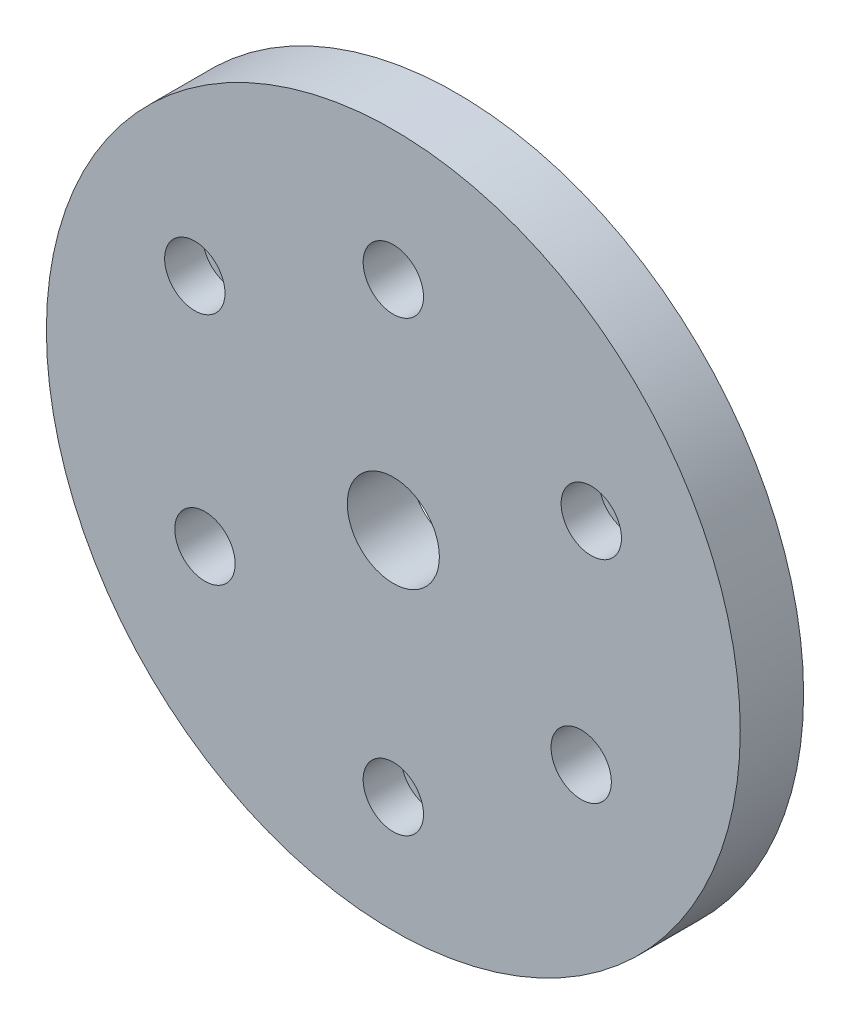
SolidWorks part; units mm, degrees
ref_plane "Plan de face" through (0, 0, 0) normal (0, 0, 1) x (1, 0, 0)
ref_plane "Plan de dessus" through (0, 0, 0) normal (0, 1, 0) x (1, 0, 0)
ref_plane "Plan de droite" through (0, 0, 0) normal (1, 0, 0) x (0, 0, -1)
sketch "Esquisse1" plane through (0, 0, 0) normal (0, 0, 1) x (1, 0, 0)
  line L0 (0, 130) -> (0, 0) construction
  line L1 (-112.612, -64.6658) -> (0, 0) construction
  line L2 (0, 0) -> (112.4376, -65.267) construction
  circle A0 centre (0, 72) radius 10
  circle A1 centre (-62.4379, -35.854) radius 10
  circle A2 centre (62.2694, -36.1458) radius 10
  circle A3 centre (0, 0) radius 15.2643
  circle A4 centre (0, 0) radius 115
  dimension "D4" = 230
  dimension "D1" = 72
  dimension "D2" = 72
  dimension "D3" = 72
extrude "Boss.-Extru.1" add sketch "Esquisse1" along normal blind 14 and the other way blind 7
hole_wizard "Chambrage pour vis à tête hexagonale M121" positions "Esquisse5" profile "Esquisse4" counterbore size "M12" standard "DIN"
sketch "Esquisse5" plane through (0, 0, 14) normal (0, 0, 1) x (1, 0, 0)
  point P0 (0, -76.5607)
  point P2 (65.6148, 35.5167)
  point P4 (-65.8039, 40.1139)
sketch "Esquisse4" plane through (0, -76.5607, 14) normal (1, 0, 0) x (0, -1, 0)
  line L0 (0, 0) -> (0, 24.0558)
  line L1 (0, 24.0558) -> (6.75, 20)
  line L2 (6.75, 20) -> (6.75, 12.6)
  line L3 (6.75, 12.6) -> (10, 12.6)
  line L4 (10, 12.6) -> (10, 0)
  line L5 (10, 0) -> (0, 0)
  line L10 (0, 24.0558) -> (-6.75, 20) construction
  line L11 (0, -6.35) -> (0, 107.95) construction
  dimension "Diamètre du perçage" = 13.5
  dimension "Profondeur du perçage" = 20
  dimension "Diamètre du chambrage" = 20
  dimension "Profondeur du chambrage" = 12.6
  dimension "Angle de pointe" = 118
scale "Echelle1" scale about centroid uniform scaling yes scale factor 0.25
